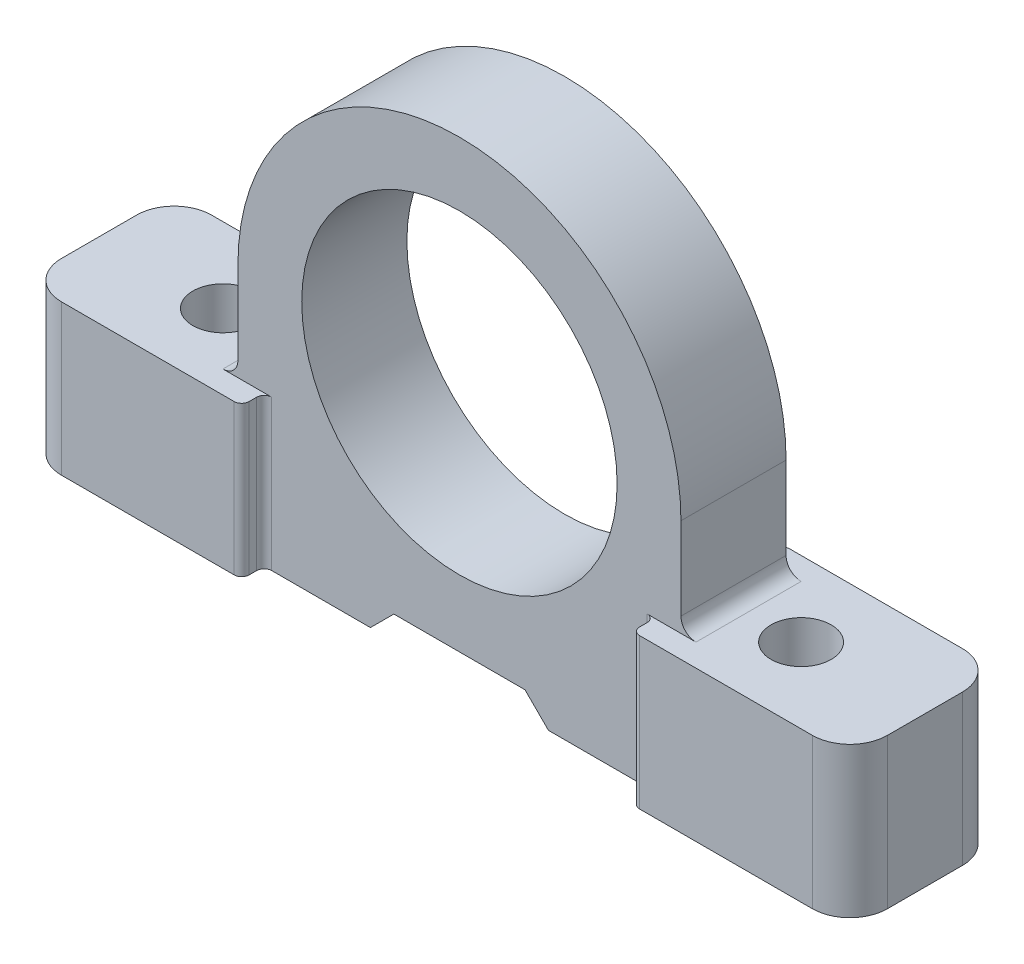
SolidWorks part; units mm, degrees
material "1023 Carbon Steel Sheet (SS)"
ref_plane "Front Plane" through (0, 0, 0) normal (0, 0, 1) x (1, 0, 0)
ref_plane "Top Plane" through (0, 0, 0) normal (0, 1, 0) x (1, 0, 0)
ref_plane "Right Plane" through (0, 0, 0) normal (1, 0, 0) x (0, 0, -1)
sketch "Sketch1" plane through (0, 0, 0) normal (0, 0, 1) x (1, 0, 0)
  line L0 (-29.5, 0) -> (-29.5, -11)
  line L1 (-31.5, -13) -> (-55, -13)
  line L2 (-55, -13) -> (-55, -33)
  line L3 (-55, -33) -> (55, -33)
  line L4 (0, -33) -> (0, 40.4072) construction
  line L5 (31.5, -13) -> (55, -13)
  line L6 (29.5, 0) -> (29.5, -11)
  line L7 (55, -13) -> (55, -33)
  arc A0 (29.5, 0) -> (-29.5, 0) centre (0, 0) ccw
  circle A1 centre (0, 0) radius 21
  arc A2 (31.5, -13) -> (29.5, -11) centre (31.5, -11) cw
  arc A3 (-29.5, -11) -> (-31.5, -13) centre (-31.5, -11) cw
  point P16 (29.5, -13)
  point P19 (-29.5, -13)
  dimension "D1" = 8.5
  dimension "D2" = 42
  dimension "D6" = 2
  dimension "D3" = 33
  dimension "D4" = 20
  dimension "D5" = 55
extrude "Boss-Extrude1" add sketch "Sketch1" along normal mid plane 14
sketch "Sketch2" plane through (0, 0, 7) normal (0, 0, 1) x (1, 0, 0)
  line L0 (-55, -33) -> (55, -33) construction
  line L1 (-55, -13) -> (-26, -13)
  line L2 (-55, -13) -> (-55, -33)
  line L3 (-55, -33) -> (-26, -33)
  line L4 (-26, -13) -> (-26, -33)
  line L5 (0, 0) -> (0, -46.9414) construction
  line L6 (55, -33) -> (26, -33)
  line L7 (26, -13) -> (26, -33)
  line L8 (55, -13) -> (26, -13)
  line L9 (55, -13) -> (55, -33)
  dimension "D1" = 29
extrude "Boss-Extrude2" add sketch "Sketch2" along normal blind 3
mirror "Mirror1" about plane through (0, 0, 0) normal (0, 0, 1) of "Boss-Extrude2"
sketch "Sketch3" plane through (0, 0, 7) normal (0, 0, 1) x (1, 0, 0)
  line L0 (0, 0) -> (0, -43.9457) construction
  line L1 (-11.8538, -33) -> (-8.7326, -29.8788)
  line L2 (-26, -33) -> (26, -33) construction
  line L3 (-8.7326, -29.8788) -> (8.7326, -29.8788)
  line L4 (8.7326, -29.8788) -> (11.8538, -33)
  line L5 (-11.8538, -33) -> (11.8538, -33)
extrude "Cut-Extrude1" cut sketch "Sketch3" against normal through all
fillet "Fillet1" radius 5 4 edges at (-55, -23, -10) (-55, -23, 10) (55, -23, -10) (55, -23, 10)
fillet "Fillet2" radius 1 8 edges at (26, -23, -10) (26, -23, -7) (-26, -23, -7) (-26, -23, -10) (-26, -23, 10) (-26, -23, 7) (26, -23, 7) (26, -23, 10)
sketch "Sketch4" plane through (0, -13, 0) normal (0, 1, 0) x (1, 0, 0)
  line L0 (0, 14.1312) -> (0, -9.3744) construction
  line L1 (38.5, 10) -> (38.5, -10) construction
  line L2 (50, 10) -> (27, 10) construction
  line L3 (50, -10) -> (27, -10) construction
  circle A0 centre (38.5, 0) radius 4
  circle A1 centre (-38.5, 0) radius 4
  dimension "D1" = 8
extrude "Cut-Extrude2" cut sketch "Sketch4" against normal through all
